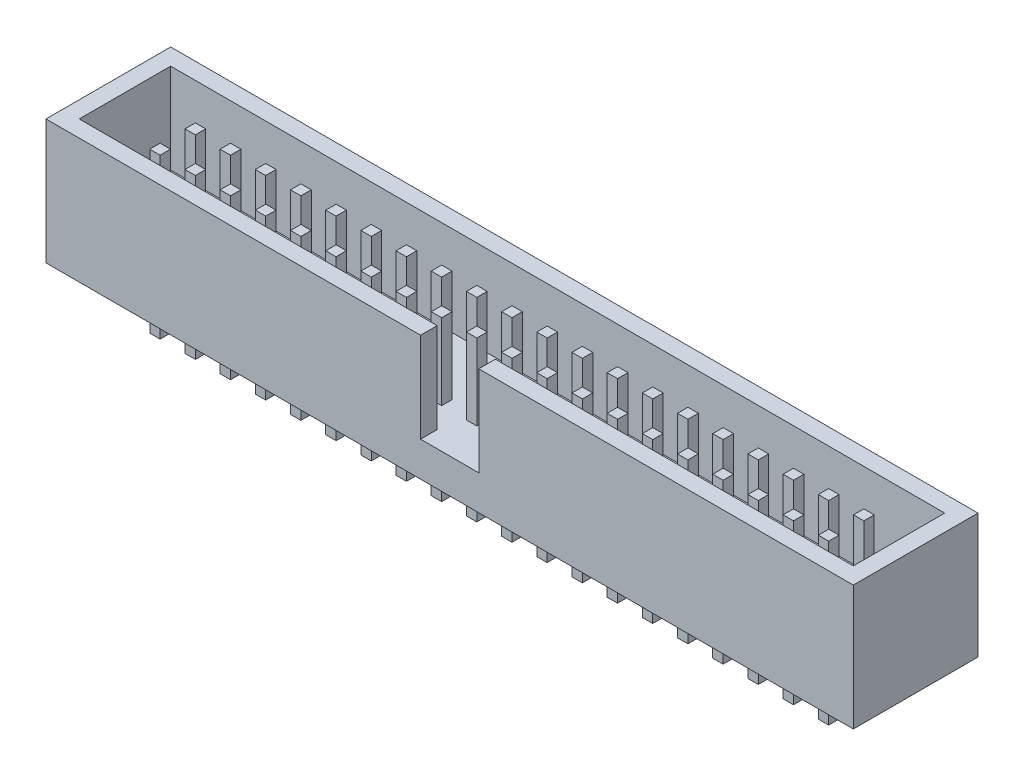
SolidWorks part; units mm, degrees
ref_plane "前视基准面" through (0, 0, 0) normal (0, 0, 1) x (1, 0, 0)
ref_plane "上视基准面" through (0, 0, 0) normal (0, 1, 0) x (1, 0, 0)
ref_plane "右视基准面" through (0, 0, 0) normal (1, 0, 0) x (0, 0, -1)
sketch "草图1" plane through (0, 0, 0) normal (0, 1, 0) x (1, 0, 0)
  line L0 (0, 85.0964) -> (0, -118.2031) construction
  line L1 (-29.14, 4.5) -> (29.14, 4.5)
  line L2 (-29.14, 4.5) -> (-29.14, -4.5)
  line L3 (-29.14, -4.5) -> (29.14, -4.5)
  line L4 (29.14, 4.5) -> (29.14, -4.5)
  line L5 (-200.5452, 0) -> (261.2352, 0) construction
  dimension "D1" = 9
  dimension "D2" = 58.28
extrude "拉伸1" add sketch "草图1" along normal blind 9
sketch "草图2" plane through (0, 9, 0) normal (0, 1, 0) x (-1, 0, 0)
  line L8 (-27.94, 3.3) -> (-27.94, -3.3)
  line L9 (27.94, 3.3) -> (-27.94, 3.3)
  line L10 (27.94, -3.3) -> (27.94, 3.3)
  line L11 (-27.94, -3.3) -> (27.94, -3.3)
  line L12 (-27.94, 3.3) -> (-27.94, -3.3)
  line L13 (27.94, 3.3) -> (-27.94, 3.3)
  line L14 (27.94, -3.3) -> (27.94, 3.3)
  line L15 (-27.94, -3.3) -> (27.94, -3.3)
  dimension "D1" = 1.2
extrude "切除-拉伸1" cut sketch "草图2" against normal blind 6.5
sketch "草图3" plane through (0, 0, 4.5) normal (0, 0, 1) x (1, 0, 0)
  line L0 (-29.14, 9) -> (29.14, 9) construction
  line L1 (-2.1, 9) -> (2.1, 9)
  line L2 (-2.1, 9) -> (-2.1, 2.5)
  line L3 (-2.1, 2.5) -> (2.1, 2.5)
  line L4 (2.1, 9) -> (2.1, 2.5)
  line L5 (-27.94, 2.5) -> (27.94, 2.5) construction
  line L6 (0, 9.4226) -> (0, -4.0288) construction
  dimension "D1" = 4.2
extrude "切除-拉伸2" cut sketch "草图3" against normal blind 6.5
sketch "草图5" plane through (0, 0, 0) normal (0, -1, 0) x (1, 0, 0)
  line L0 (0, 6.0683) -> (0, -6.9786) construction
  line L1 (-14.7999, 0) -> (15.2382, 0) construction
  line L2 (-1.27, 2.5244) -> (-1.27, -0.4442) construction
  line L3 (-1.645, 0.895) -> (-0.895, 0.895)
  line L4 (-1.645, 0.895) -> (-1.645, 1.645)
  line L5 (-1.645, 1.645) -> (-0.895, 1.645)
  line L6 (-0.895, 0.895) -> (-0.895, 1.645)
  line L7 (-2.3518, 1.27) -> (0.5396, 1.27) construction
  line L8 (-4.185, 0.895) -> (-3.435, 0.895)
  line L9 (-4.185, 0.895) -> (-4.185, 1.645)
  line L10 (-4.185, 1.645) -> (-3.435, 1.645)
  line L11 (-3.435, 0.895) -> (-3.435, 1.645)
  line L12 (-6.725, 0.895) -> (-5.975, 0.895)
  line L13 (-6.725, 0.895) -> (-6.725, 1.645)
  line L14 (-6.725, 1.645) -> (-5.975, 1.645)
  line L15 (-5.975, 0.895) -> (-5.975, 1.645)
  line L16 (-9.265, 0.895) -> (-8.515, 0.895)
  line L17 (-9.265, 0.895) -> (-9.265, 1.645)
  line L18 (-9.265, 1.645) -> (-8.515, 1.645)
  line L19 (-8.515, 0.895) -> (-8.515, 1.645)
  line L20 (-8.515, -0.895) -> (-8.515, -1.645)
  line L21 (-9.265, -1.645) -> (-8.515, -1.645)
  line L22 (-9.265, -0.895) -> (-9.265, -1.645)
  line L23 (-9.265, -0.895) -> (-8.515, -0.895)
  line L24 (-5.975, -0.895) -> (-5.975, -1.645)
  line L25 (-6.725, -1.645) -> (-5.975, -1.645)
  line L26 (-6.725, -0.895) -> (-6.725, -1.645)
  line L27 (-6.725, -0.895) -> (-5.975, -0.895)
  line L28 (-3.435, -0.895) -> (-3.435, -1.645)
  line L29 (-4.185, -1.645) -> (-3.435, -1.645)
  line L30 (-4.185, -0.895) -> (-4.185, -1.645)
  line L31 (-4.185, -0.895) -> (-3.435, -0.895)
  line L32 (-0.895, -0.895) -> (-0.895, -1.645)
  line L33 (-1.645, -1.645) -> (-0.895, -1.645)
  line L34 (-1.645, -0.895) -> (-1.645, -1.645)
  line L35 (-1.645, -0.895) -> (-0.895, -0.895)
  line L36 (1.27, 2.5244) -> (1.27, -0.4442) construction
  line L37 (1.645, -0.895) -> (0.895, -0.895)
  line L38 (1.645, -0.895) -> (1.645, -1.645)
  line L39 (1.645, -1.645) -> (0.895, -1.645)
  line L40 (0.895, -0.895) -> (0.895, -1.645)
  line L41 (4.185, -0.895) -> (3.435, -0.895)
  line L42 (4.185, -0.895) -> (4.185, -1.645)
  line L43 (4.185, -1.645) -> (3.435, -1.645)
  line L44 (3.435, -0.895) -> (3.435, -1.645)
  line L45 (6.725, -0.895) -> (5.975, -0.895)
  line L46 (6.725, -0.895) -> (6.725, -1.645)
  line L47 (6.725, -1.645) -> (5.975, -1.645)
  line L48 (5.975, -0.895) -> (5.975, -1.645)
  line L49 (9.265, -0.895) -> (8.515, -0.895)
  line L50 (9.265, -0.895) -> (9.265, -1.645)
  line L51 (9.265, -1.645) -> (8.515, -1.645)
  line L52 (8.515, -0.895) -> (8.515, -1.645)
  line L53 (8.515, 0.895) -> (8.515, 1.645)
  line L54 (9.265, 1.645) -> (8.515, 1.645)
  line L55 (9.265, 0.895) -> (9.265, 1.645)
  line L56 (9.265, 0.895) -> (8.515, 0.895)
  line L57 (5.975, 0.895) -> (5.975, 1.645)
  line L58 (6.725, 1.645) -> (5.975, 1.645)
  line L59 (6.725, 0.895) -> (6.725, 1.645)
  line L60 (6.725, 0.895) -> (5.975, 0.895)
  line L61 (3.435, 0.895) -> (3.435, 1.645)
  line L62 (4.185, 1.645) -> (3.435, 1.645)
  line L63 (4.185, 0.895) -> (4.185, 1.645)
  line L64 (4.185, 0.895) -> (3.435, 0.895)
  line L65 (0.895, 0.895) -> (0.895, 1.645)
  line L66 (1.645, 1.645) -> (0.895, 1.645)
  line L67 (1.645, 0.895) -> (1.645, 1.645)
  line L68 (1.645, 0.895) -> (0.895, 0.895)
  line L69 (11.805, -0.895) -> (11.055, -0.895)
  line L70 (11.805, -0.895) -> (11.805, -1.645)
  line L71 (11.805, -1.645) -> (11.055, -1.645)
  line L72 (11.055, -0.895) -> (11.055, -1.645)
  line L73 (11.055, 0.895) -> (11.055, 1.645)
  line L74 (11.805, 1.645) -> (11.055, 1.645)
  line L75 (11.805, 0.895) -> (11.805, 1.645)
  line L76 (11.805, 0.895) -> (11.055, 0.895)
  line L77 (14.345, -0.895) -> (13.595, -0.895)
  line L78 (14.345, -0.895) -> (14.345, -1.645)
  line L79 (14.345, -1.645) -> (13.595, -1.645)
  line L80 (13.595, -0.895) -> (13.595, -1.645)
  line L81 (13.595, 0.895) -> (13.595, 1.645)
  line L82 (14.345, 1.645) -> (13.595, 1.645)
  line L83 (14.345, 0.895) -> (14.345, 1.645)
  line L84 (14.345, 0.895) -> (13.595, 0.895)
  line L85 (16.885, -0.895) -> (16.135, -0.895)
  line L86 (16.885, -0.895) -> (16.885, -1.645)
  line L87 (16.885, -1.645) -> (16.135, -1.645)
  line L88 (16.135, -0.895) -> (16.135, -1.645)
  line L89 (16.135, 0.895) -> (16.135, 1.645)
  line L90 (16.885, 1.645) -> (16.135, 1.645)
  line L91 (16.885, 0.895) -> (16.885, 1.645)
  line L92 (16.885, 0.895) -> (16.135, 0.895)
  line L93 (19.425, -0.895) -> (18.675, -0.895)
  line L94 (19.425, -0.895) -> (19.425, -1.645)
  line L95 (19.425, -1.645) -> (18.675, -1.645)
  line L96 (18.675, -0.895) -> (18.675, -1.645)
  line L97 (18.675, 0.895) -> (18.675, 1.645)
  line L98 (19.425, 1.645) -> (18.675, 1.645)
  line L99 (19.425, 0.895) -> (19.425, 1.645)
  line L100 (19.425, 0.895) -> (18.675, 0.895)
  line L101 (21.965, -0.895) -> (21.215, -0.895)
  line L102 (21.965, -0.895) -> (21.965, -1.645)
  line L103 (21.965, -1.645) -> (21.215, -1.645)
  line L104 (21.215, -0.895) -> (21.215, -1.645)
  line L105 (21.215, 0.895) -> (21.215, 1.645)
  line L106 (21.965, 1.645) -> (21.215, 1.645)
  line L107 (21.965, 0.895) -> (21.965, 1.645)
  line L108 (21.965, 0.895) -> (21.215, 0.895)
  line L109 (24.505, -0.895) -> (23.755, -0.895)
  line L110 (24.505, -0.895) -> (24.505, -1.645)
  line L111 (24.505, -1.645) -> (23.755, -1.645)
  line L112 (23.755, -0.895) -> (23.755, -1.645)
  line L113 (23.755, 0.895) -> (23.755, 1.645)
  line L114 (24.505, 1.645) -> (23.755, 1.645)
  line L115 (24.505, 0.895) -> (24.505, 1.645)
  line L116 (24.505, 0.895) -> (23.755, 0.895)
  line L117 (-11.805, 0.895) -> (-11.055, 0.895)
  line L118 (-11.805, 0.895) -> (-11.805, 1.645)
  line L119 (-11.805, 1.645) -> (-11.055, 1.645)
  line L120 (-11.055, 0.895) -> (-11.055, 1.645)
  line L121 (-11.055, -0.895) -> (-11.055, -1.645)
  line L122 (-11.805, -1.645) -> (-11.055, -1.645)
  line L123 (-11.805, -0.895) -> (-11.805, -1.645)
  line L124 (-11.805, -0.895) -> (-11.055, -0.895)
  line L125 (-14.345, 0.895) -> (-13.595, 0.895)
  line L126 (-14.345, 0.895) -> (-14.345, 1.645)
  line L127 (-14.345, 1.645) -> (-13.595, 1.645)
  line L128 (-13.595, 0.895) -> (-13.595, 1.645)
  line L129 (-13.595, -0.895) -> (-13.595, -1.645)
  line L130 (-14.345, -1.645) -> (-13.595, -1.645)
  line L131 (-14.345, -0.895) -> (-14.345, -1.645)
  line L132 (-14.345, -0.895) -> (-13.595, -0.895)
  line L133 (-16.885, 0.895) -> (-16.135, 0.895)
  line L134 (-16.885, 0.895) -> (-16.885, 1.645)
  line L135 (-16.885, 1.645) -> (-16.135, 1.645)
  line L136 (-16.135, 0.895) -> (-16.135, 1.645)
  line L137 (-16.135, -0.895) -> (-16.135, -1.645)
  line L138 (-16.885, -1.645) -> (-16.135, -1.645)
  line L139 (-16.885, -0.895) -> (-16.885, -1.645)
  line L140 (-16.885, -0.895) -> (-16.135, -0.895)
  line L141 (-19.425, 0.895) -> (-18.675, 0.895)
  line L142 (-19.425, 0.895) -> (-19.425, 1.645)
  line L143 (-19.425, 1.645) -> (-18.675, 1.645)
  line L144 (-18.675, 0.895) -> (-18.675, 1.645)
  line L145 (-18.675, -0.895) -> (-18.675, -1.645)
  line L146 (-19.425, -1.645) -> (-18.675, -1.645)
  line L147 (-19.425, -0.895) -> (-19.425, -1.645)
  line L148 (-19.425, -0.895) -> (-18.675, -0.895)
  line L149 (-21.965, 0.895) -> (-21.215, 0.895)
  line L150 (-21.965, 0.895) -> (-21.965, 1.645)
  line L151 (-21.965, 1.645) -> (-21.215, 1.645)
  line L152 (-21.215, 0.895) -> (-21.215, 1.645)
  line L153 (-21.215, -0.895) -> (-21.215, -1.645)
  line L154 (-21.965, -1.645) -> (-21.215, -1.645)
  line L155 (-21.965, -0.895) -> (-21.965, -1.645)
  line L156 (-21.965, -0.895) -> (-21.215, -0.895)
  line L157 (-24.505, 0.895) -> (-23.755, 0.895)
  line L158 (-24.505, 0.895) -> (-24.505, 1.645)
  line L159 (-24.505, 1.645) -> (-23.755, 1.645)
  line L160 (-23.755, 0.895) -> (-23.755, 1.645)
  line L161 (-23.755, -0.895) -> (-23.755, -1.645)
  line L162 (-24.505, -1.645) -> (-23.755, -1.645)
  line L163 (-24.505, -0.895) -> (-24.505, -1.645)
  line L164 (-24.505, -0.895) -> (-23.755, -0.895)
  dimension "D1" = 0.75
  dimension "D2" = 0.75
  dimension "D3" = 1.27
  dimension "D4" = 1.27
extrude "拉伸2" add sketch "草图5" along normal blind 3.5 and the other way offset from surface (8 mm away) 1 other way up to face at (0, 9, 1.3)
sketch "草图6" plane through (0, 0, 0) normal (0, -1, 0) x (1, 0, 0)
  line L0 (34.2898, 0) -> (-33.2336, 0) construction
  line L1 (0, 6.8981) -> (0, -7.2913) construction
  line L10 (24.505, 0.895) -> (24.505, 1.645) construction
  line L11 (24.505, 1.645) -> (23.755, 1.645) construction
  line L13 (23.755, 0.895) -> (24.505, 0.895) construction
  circle A0 centre (24.13, 1.27) radius 0.375
